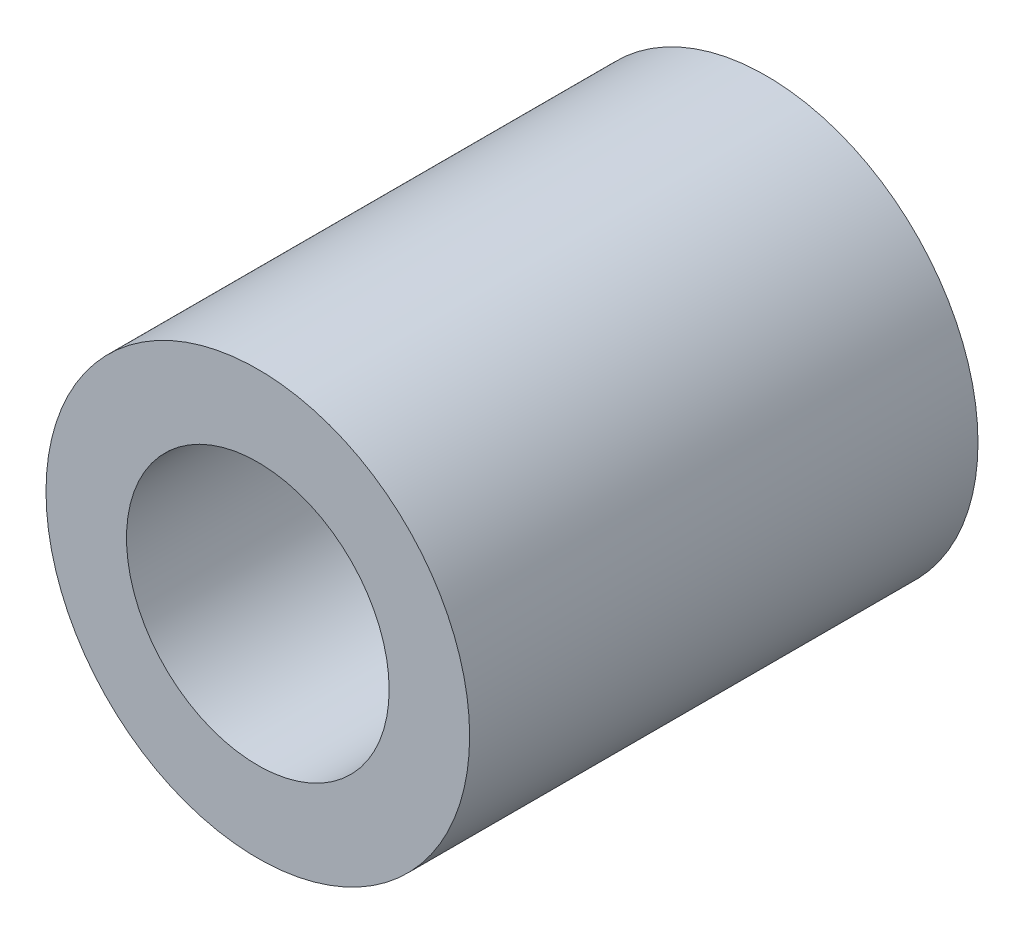
SolidWorks part; units mm, degrees
ref_plane "Płaszczyzna przednia" through (0, 0, 0) normal (0, 0, 1) x (1, 0, 0)
ref_plane "Płaszczyzna górna" through (0, 0, 0) normal (0, 1, 0) x (1, 0, 0)
ref_plane "Płaszczyzna prawa" through (0, 0, 0) normal (1, 0, 0) x (0, 0, -1)
sketch "Szkic1" plane through (0, 0, 0) normal (0, 0, 1) x (1, 0, 0)
  circle A0 centre (-115.1857, 88.596) radius 2.5
  circle A1 centre (-115.1857, 88.596) radius 1.55
  dimension "D1" = 3.1
  dimension "D2" = 5
extrude "Dodanie-wyciągnięcie1" add sketch "Szkic1" along normal blind 6
